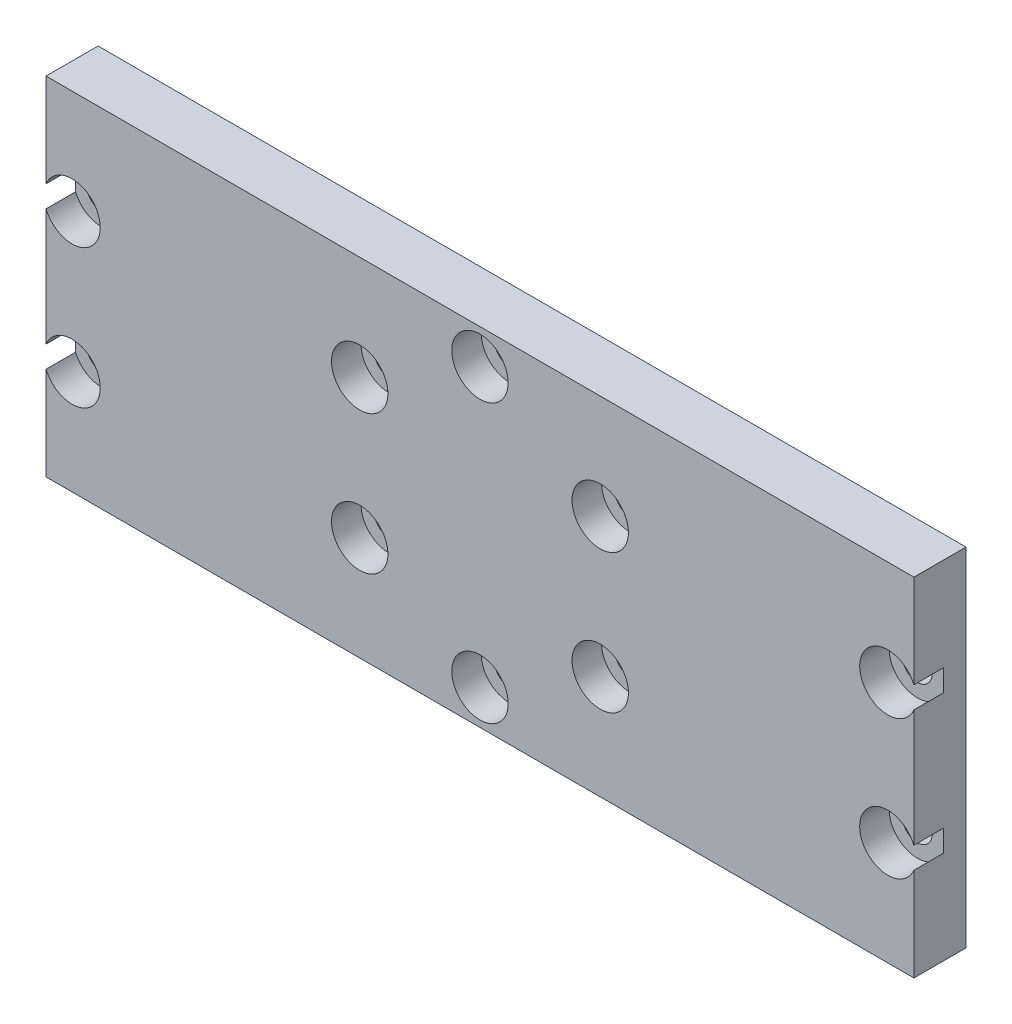
SolidWorks part; units mm, degrees
ref_plane "Front Plane" through (0, 0, 0) normal (0, 0, 1) x (1, 0, 0)
ref_plane "Top Plane" through (0, 0, 0) normal (0, 1, 0) x (1, 0, 0)
ref_plane "Right Plane" through (0, 0, 0) normal (1, 0, 0) x (0, 0, -1)
sketch "Sketch1" plane through (0, 0, 0) normal (0, 0, 1) x (1, 0, 0)
  line L1 (0, 0) -> (100, 0)
  line L2 (0, 0) -> (0, 40)
  line L3 (0, 40) -> (100, 40)
  line L4 (100, 0) -> (100, 40)
  dimension "D1" = 40
  dimension "D2" = 100
extrude "Boss-Extrude1" add sketch "Sketch1" along normal blind 6
sketch "Sketch2" plane through (0, 0, 6) normal (0, 0, 1) x (1, 0, 0)
  line L0 (3, 28) -> (3, 12)
  line L2 (3, 20) -> (0, 20) construction
  line L3 (0, 40) -> (0, 0) construction
  point P0 (3, 28)
  point P7 (97, 28)
  point P8 (97, 12)
  point P9 (3, 12)
  dimension "D3" = 16
  dimension "D4" = 94
  dimension "D5" = 3
  dimension "D2" = 2
  dimension "D1" = 2
hole_wizard "CBORE for M3 Hex Socket Head Cap Screw1" positions "Sketch2" profile "Sketch4" counterbore size "M3" standard "DIN" end condition through all
sketch "Sketch4" plane through (3, 28, 6) normal (1, 0, 0) x (0, -1, 0)
  line L0 (0, 0) -> (0, 6)
  line L1 (0, 6) -> (1.7, 6)
  line L3 (1.7, 6) -> (1.7, 3.4)
  line L4 (1.7, 3.4) -> (3.25, 3.4)
  line L5 (3.25, 3.4) -> (3.25, 0)
  line L7 (3.25, 0) -> (0, 0)
  line L11 (0, -6.35) -> (0, 107.95) construction
  dimension "Thru Hole Dia." = 3.4
  dimension "Thru Hole Depth" = 6
  dimension "C'Bore Dia." = 6.5
  dimension "C'Bore Depth" = 3.4
sketch "Sketch5" plane through (0, 0, 6) normal (0, 0, 1) x (1, 0, 0)
  line L0 (0, 40) -> (100, 0) construction
  line L1 (100, 0) -> (100, 40) construction
  line L2 (100, 40) -> (0, 0) construction
  circle A0 centre (50, 20) radius 16 construction
  point P16 (50, 36)
  point P23 (63.8564, 28)
  point P24 (63.8564, 12)
  point P25 (50, 4)
  point P26 (36.1436, 12)
  point P27 (36.1436, 28)
  dimension "D1" = 32
hole_wizard "CBORE for M3 Hex Socket Head Cap Screw2" positions "Sketch5" profile "Sketch6" counterbore size "M3" standard "DIN" end condition through all
sketch "Sketch6" plane through (36.1436, 28, 6) normal (1, 0, 0) x (0, -1, 0)
  line L0 (0, 0) -> (0, 6)
  line L1 (0, 6) -> (1.7, 6)
  line L3 (1.7, 6) -> (1.7, 3.4)
  line L4 (1.7, 3.4) -> (3.25, 3.4)
  line L5 (3.25, 3.4) -> (3.25, 0)
  line L7 (3.25, 0) -> (0, 0)
  line L11 (0, -6.35) -> (0, 107.95) construction
  dimension "Thru Hole Dia." = 3.4
  dimension "Thru Hole Depth" = 6
  dimension "C'Bore Dia." = 6.5
  dimension "C'Bore Depth" = 3.4
